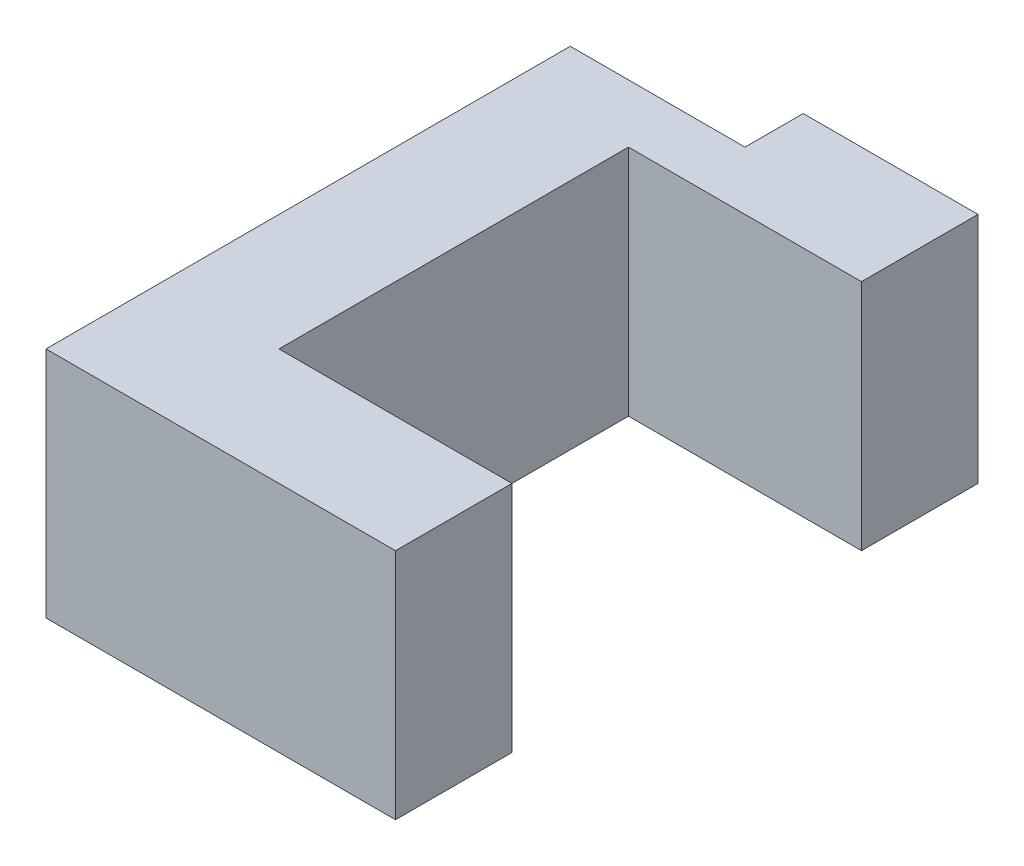
SolidWorks part; units mm, degrees
ref_plane "Přední rovina" through (0, 0, 0) normal (0, 0, 1) x (1, 0, 0)
ref_plane "Horní rovina" through (0, 0, 0) normal (0, 1, 0) x (1, 0, 0)
ref_plane "Pravá rovina" through (0, 0, 0) normal (1, 0, 0) x (0, 0, -1)
sketch "Sketch1" plane through (0, 0, 0) normal (0, 1, 0) x (1, 0, 0)
  line L0 (0, 0) -> (0, -50)
  line L1 (0, -50) -> (30, -50)
  line L2 (30, -50) -> (30, -40)
  line L3 (30, -40) -> (10, -40)
  line L4 (10, -40) -> (10, -10)
  line L5 (10, -10) -> (30, -10)
  line L6 (30, -10) -> (30, 0)
  line L7 (30, 0) -> (0, 0)
  dimension "D1" = 10
  dimension "D2" = 10
  dimension "D3" = 30
  dimension "D4" = 10
  dimension "D5" = 20
extrude "Boss-Extrude1" add sketch "Sketch1" along normal blind 20
sketch "Sketch3" plane through (0, 20, 0) normal (0, 1, 0) x (1, 0, 0)
  line L1 (0, 0) -> (15.0006, 0)
  line L2 (0, 0) -> (0, -5)
  line L3 (0, -5) -> (15.0006, -5)
  line L4 (15.0006, 0) -> (15.0006, -5)
  dimension "D1" = 5
  dimension "D2" = 15.0006
extrude "Cut-Extrude2" cut sketch "Sketch3" against normal blind 18
equation "\"H\"= 30"
equation "\"D3@Sketch1\"=\"H\""
equation "\"L\"= 20"
equation "\"D5@Sketch1\"=\"L\""
